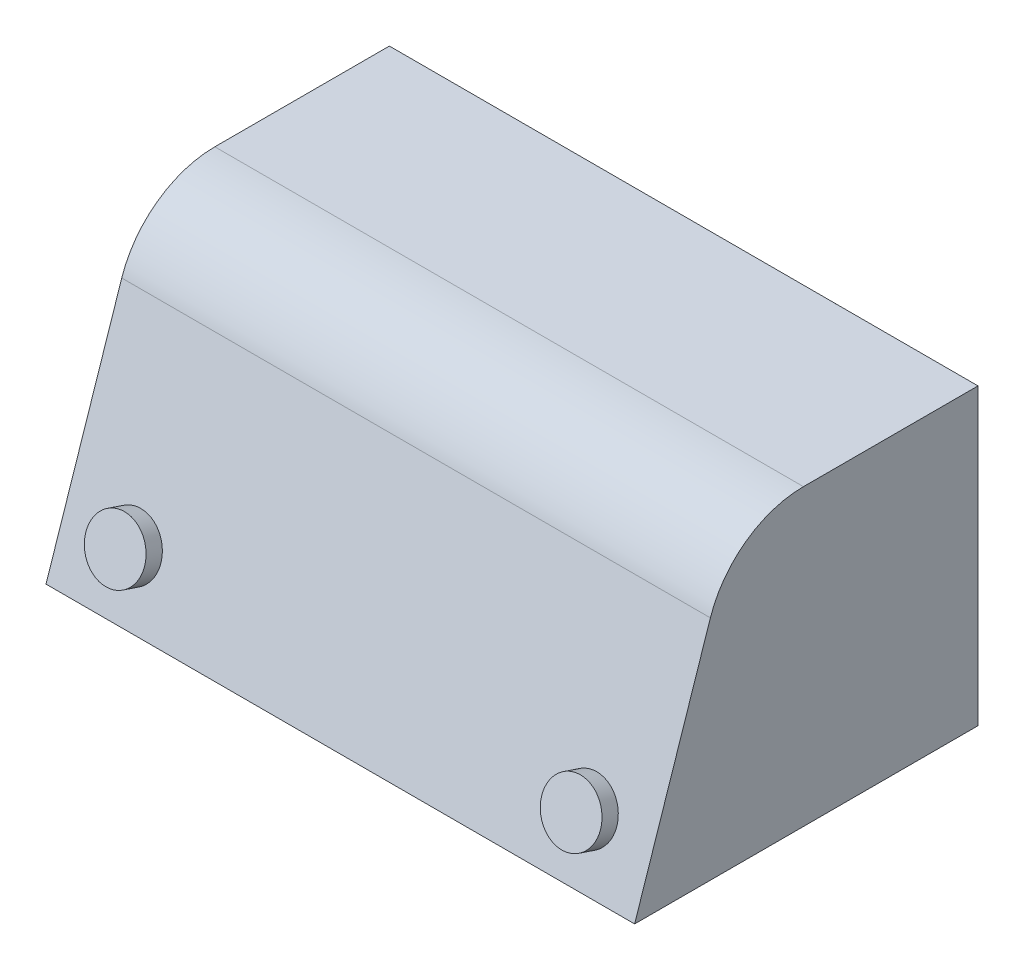
SolidWorks part; units mm, degrees
ref_plane "Front Plane" through (0, 0, 0) normal (0, 0, 1) x (1, 0, 0)
ref_plane "Top Plane" through (0, 0, 0) normal (0, 1, 0) x (1, 0, 0)
ref_plane "Right Plane" through (0, 0, 0) normal (1, 0, 0) x (0, 0, -1)
sketch "Sketch1" plane through (0, 0, 0) normal (1, 0, 0) x (0, 0, -1)
  line L0 (-70, 0) -> (0, 0)
  line L1 (0, 0) -> (0, 60)
  line L2 (0, 60) -> (-50, 60)
  line L3 (-50, 60) -> (-70, 0)
  dimension "D1" = 70
  dimension "D2" = 60
  dimension "D3" = 50
extrude "Boss-Extrude1" add sketch "Sketch1" along normal blind 120
fillet "Fillet2" radius 20 1 edges at (60, 60, 50)
sketch "Sketch2" plane through (0, 21, 63) normal (0, 0.3162, 0.9487) x (1, 0, 0)
  circle A0 centre (13.5701, -9.9358) radius 6
  circle A1 centre (106.5192, -9.9358) radius 6
  dimension "D1" = 12
  dimension "D2" = 12
extrude "Boss-Extrude2" add sketch "Sketch2" along normal blind 3.5
